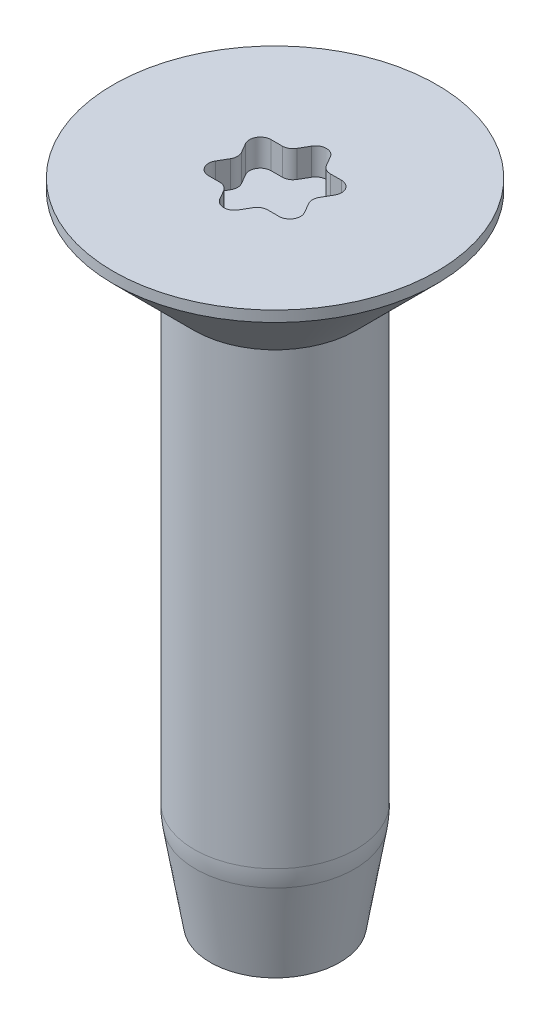
SolidWorks part; units mm, degrees
ref_plane "Front" through (0, 0, 0) normal (0, 0, 1) x (1, 0, 0)
ref_plane "Top" through (0, 0, 0) normal (0, 1, 0) x (1, 0, 0)
ref_plane "Right" through (0, 0, 0) normal (1, 0, 0) x (0, 0, -1)
sketch "Sketch1" plane through (0, 0, 0) normal (0, 0, 1) x (1, 0, 0)
  line L0 (0, 0) -> (0, 1.7)
  line L1 (0, 1.7) -> (3, 1.7)
  line L2 (3, 1.5) -> (1.5, 0)
  line L3 (1.5, 0) -> (0, 0)
  line L4 (0, 0) -> (0, -1.6816) construction
  line L5 (3, 1.5) -> (3, 1.7)
  point P2 (3.2, 1.7)
  dimension "D1" = 1.7
  dimension "D2" = 45
  dimension "D3" = 3
  dimension "D4" = 6
  dimension "D5" = 6.4
ref_axis "Axis1" through (0, 50, 0) along (0, -1, 0)
revolve "Revolve1" add sketch "Sketch1" angle 360 about axis through (0, 50, 0) along (0, -1, 0)
sketch "Sketch2" plane through (0, 0, 0) normal (0, -1, 0) x (1, 0, 0)
  circle A0 centre (0, 0) radius 1.5
  dimension "D1" = 3
extrude "Boss-Extrude1" add sketch "Sketch2" along normal offset from surface (10.3 mm away) 12 up to face at (0, 1.7, 3)
sketch "Sketch3" plane through (0, 0, 0) normal (0, 0, 1) x (1, 0, 0)
  line L0 (0, 0) -> (0, -11.7224) construction
  line L1 (1.5, -8.5) -> (1.2, -10.3)
  line L2 (1.2, -10.3) -> (1.5, -10.3)
  line L3 (1.5, -10.3) -> (1.5, -8.5)
  line L4 (1.5, -10.3) -> (1.5, 0) construction
  line L5 (-1.5, -10.3) -> (1.5, -10.3) construction
  dimension "D1" = 0.3
  dimension "D2" = 1.8
revolve "Cut-Revolve1" cut sketch "Sketch3" angle 360 about L0
sketch "Sketch4" plane through (0, 1.7, 0) normal (0, 1, 0) x (1, 0, 0)
  line L0 (0, 0) -> (0, 1.9842) construction
  line L1 (0, 0) -> (2.0052, 0) construction
  line L2 (0, 1.1521) -> (0.3303, 0.58)
  line L3 (0, 1.1521) -> (-0.3303, 0.58)
  line L4 (-1, 0.58) -> (-0.3303, 0.58)
  line L5 (1, 0.58) -> (0.6651, 0)
  line L6 (-1, 0.58) -> (-0.6651, 0)
  line L7 (-1, -0.58) -> (-0.3303, -0.58)
  line L8 (-0.6651, 0) -> (-1, -0.58)
  line L9 (-0.3303, -0.58) -> (0, -1.1521)
  line L10 (0.3303, 0.58) -> (1, 0.58)
  line L11 (0.3303, -0.58) -> (0, -1.1521)
  line L12 (0.6651, 0) -> (1, -0.58)
  line L13 (0.3303, -0.58) -> (1, -0.58)
  dimension "D1" = 2
  dimension "D2" = 0.58
extrude "Cut-Extrude1" cut sketch "Sketch4" against normal blind 0.5
fillet "Fillet1" radius 0.2 12 edges at (1, 1.45, -0.58) (0.6651, 1.45, 0) (1, 1.45, 0.58) (0.3303, 1.45, 0.58) (0, 1.45, 1.1521) (-0.3303, 1.45, 0.58) (-1, 1.45, 0.58) (-0.6651, 1.45, 0) (-1, 1.45, -0.58) (0.3303, 1.45, -0.58) (0, 1.45, -1.1521) (-0.3303, 1.45, -0.58)
fillet "Fillet3" radius 2 1 edges at (-1.5, -8.5, 0)
